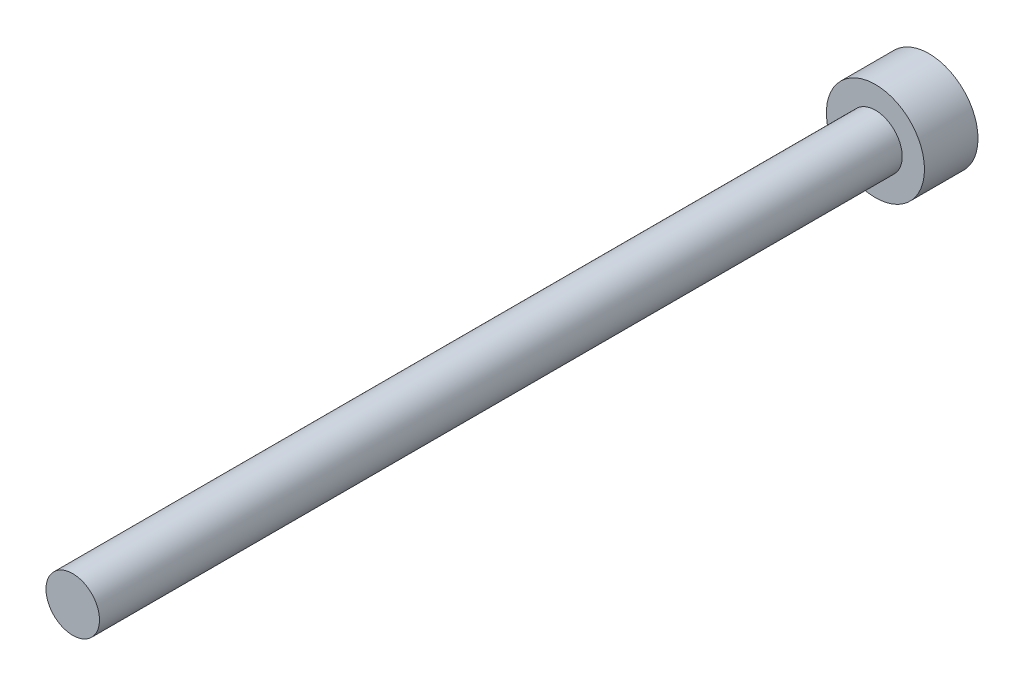
SolidWorks part; units mm, degrees
ref_plane "Front Plane" through (0, 0, 0) normal (0, 0, 1) x (1, 0, 0)
ref_plane "Top Plane" through (0, 0, 0) normal (0, 1, 0) x (1, 0, 0)
ref_plane "Right Plane" through (0, 0, 0) normal (1, 0, 0) x (0, 0, -1)
sketch "S01 - Head" plane through (0, 0, 0) normal (0, 0, 1) x (1, 0, 0)
  circle A0 centre (0, 0) radius 2.75
  dimension "D1" = 5.5
extrude "01 - Head" add sketch "S01 - Head" along normal blind 3 from offset 3
sketch "S02 - Nominal shank" plane through (0, 0, 0) normal (0, 0, 1) x (1, 0, 0)
  circle A0 centre (0, 0) radius 1.5
  dimension "D1" = 3
extrude "02 - Nominal shank" add sketch "S02 - Nominal shank" along normal blind 45
sketch "S03 - Hex key socket" plane through (0, 0, 0) normal (0, 0, 1) x (1, 0, 0)
  line L0 (1.4434, 0) -> (0.7217, 1.25)
  line L1 (0.7217, 1.25) -> (-0.7217, 1.25)
  line L2 (-0.7217, 1.25) -> (-1.4434, 0)
  line L3 (-1.4434, 0) -> (-0.7217, -1.25)
  line L4 (-0.7217, -1.25) -> (0.7217, -1.25)
  line L5 (0.7217, -1.25) -> (1.4434, 0)
  dimension "D1" = 0.7217
  dimension "D2" = 1.4434
  dimension "D3" = 0.7217
  dimension "D4" = 1.4434
  dimension "D5" = 1.25
  dimension "D6" = 1.25
extrude "03 - Hex key socket" cut sketch "S03 - Hex key socket" along normal blind 1.75 from offset 3.1
